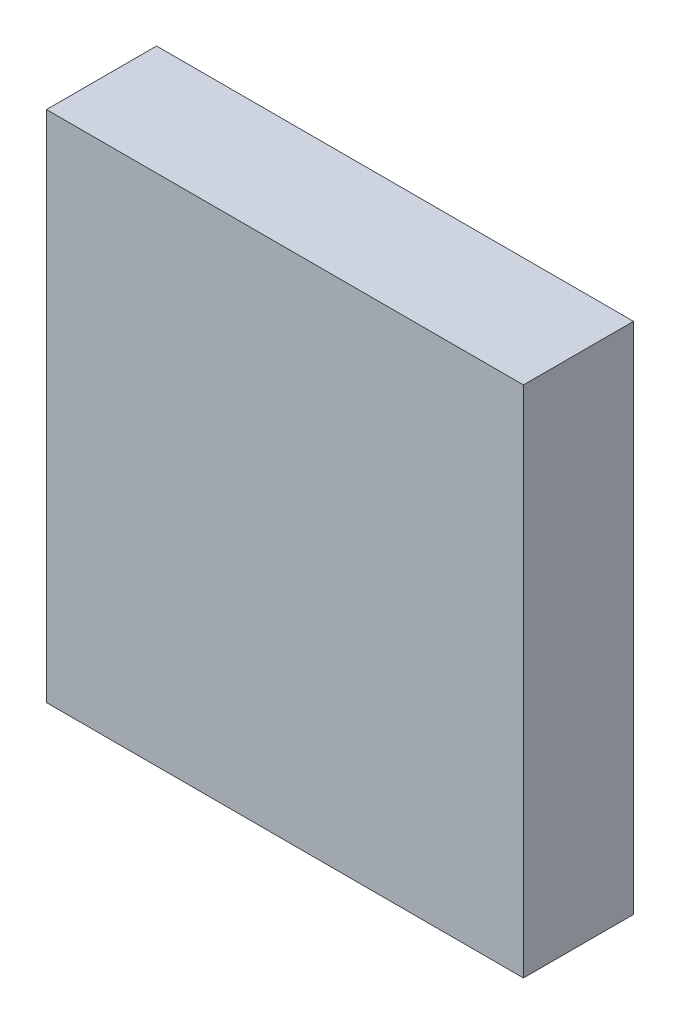
SolidWorks part; units mm, degrees
ref_plane "Front Plane" through (0, 0, 0) normal (0, 0, 1) x (1, 0, 0)
ref_plane "Top Plane" through (0, 0, 0) normal (0, 1, 0) x (1, 0, 0)
ref_plane "Right Plane" through (0, 0, 0) normal (1, 0, 0) x (0, 0, -1)
sketch "Sketch1" plane through (0, 0, 0) normal (0, 0, 1) x (1, 0, 0)
  line L1 (0, 0) -> (13, 0)
  line L2 (0, 0) -> (0, 14)
  line L3 (0, 14) -> (13, 14)
  line L4 (13, 0) -> (13, 14)
  dimension "D1" = 13
  dimension "D2" = 14
extrude "Boss-Extrude1" add sketch "Sketch1" along normal blind 3
